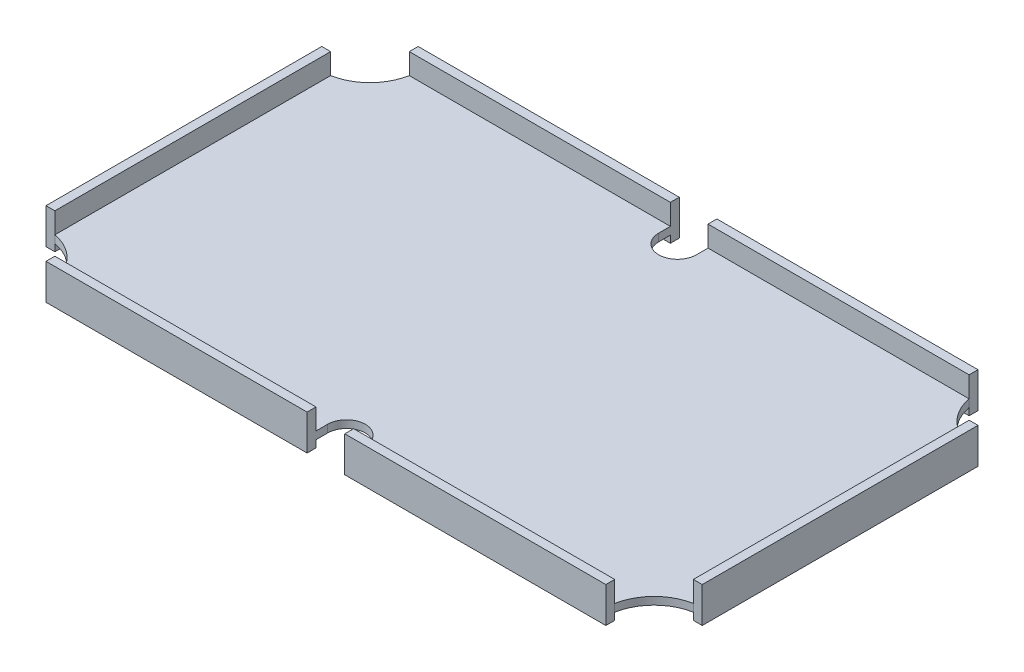
SolidWorks part; units mm, degrees
ref_plane "Alzado" through (0, 0, 0) normal (0, 0, 1) x (1, 0, 0)
ref_plane "Planta" through (0, 0, 0) normal (0, 1, 0) x (1, 0, 0)
ref_plane "Vista lateral" through (0, 0, 0) normal (1, 0, 0) x (0, 0, -1)
sketch "Croquis1" plane through (0, 0, 0) normal (0, 1, 0) x (1, 0, 0)
  line L1 (-46.2, 26.2) -> (46.2, 26.2)
  line L2 (-46.2, 26.2) -> (-46.2, -26.2)
  line L3 (-46.2, -26.2) -> (46.2, -26.2)
  line L4 (46.2, 26.2) -> (46.2, -26.2)
  line L5 (-46.2, 26.2) -> (46.2, -26.2) construction
  line L6 (-46.2, -26.2) -> (46.2, 26.2) construction
  point P0 (0, 0)
  dimension "D1" = 92.4
  dimension "D2" = 52.4
extrude "Saliente-Extruir1" add sketch "Croquis1" along normal blind 5
sketch "Croquis2" plane through (0, 5, 0) normal (0, 1, 0) x (1, 0, 0)
  line L0 (-46.2, 26.2) -> (-46.2, -26.2) construction
  line L1 (44.95, 24.95) -> (-44.95, 24.95)
  line L2 (44.95, 24.95) -> (44.95, -24.95)
  line L3 (44.95, -24.95) -> (-44.95, -24.95)
  line L4 (-44.95, 24.95) -> (-44.95, -24.95)
  line L5 (44.95, 24.95) -> (-44.95, -24.95) construction
  line L6 (44.95, -24.95) -> (-44.95, 24.95) construction
  line L7 (-46.2, -26.2) -> (46.2, -26.2) construction
  point P0 (0, 0)
  dimension "D1" = 1.25
  dimension "D2" = 1.25
extrude "Cortar-Extruir1" cut sketch "Croquis2" against normal blind 2.93
sketch "Croquis3" plane through (0, 2.07, 0) normal (0, 1, 0) x (1, 0, 0)
  line L0 (0, -20.66) -> (0, -26.2) construction
  line L2 (-46.2, -26.2) -> (46.2, -26.2) construction
  line L3 (-44.95, -24.95) -> (44.95, -24.95) construction
  line L4 (2.65, -23.31) -> (-2.65, -23.31) construction
  line L5 (2.65, -23.31) -> (2.65, -26.2)
  line L6 (2.65, -26.2) -> (-2.65, -26.2)
  line L7 (-2.65, -23.31) -> (-2.65, -26.2)
  line L8 (2.65, -23.31) -> (-2.65, -26.2) construction
  line L9 (2.65, -26.2) -> (-2.65, -23.31) construction
  arc A0 (-2.65, -23.31) -> (2.65, -23.31) centre (0, -23.31) cw
  point P3 (0, -24.755)
  dimension "D1" = 5.3
  dimension "D2" = 1.64
extrude "Cortar-Extruir2" cut sketch "Croquis3" against normal up to surface and the other way up to surface
sketch "Croquis4" plane through (0, 2.07, 0) normal (0, 1, 0) x (1, 0, 0)
  line L0 (-46.2, 26.2) -> (-46.2, -26.2) construction
  line L1 (-46.2, -26.2) -> (-2.65, -26.2) construction
  line L2 (-46.2, 26.2) -> (-46.2, -26.2) construction
  line L3 (-46.2, -26.2) -> (-2.65, -26.2) construction
  line L5 (-46.2, -19.4142) -> (-46.2, -26.2)
  line L6 (-46.2, -26.2) -> (-39.4142, -26.2)
  line L7 (-44.95, 24.95) -> (-44.95, -24.95) construction
  line L8 (-44.95, -24.95) -> (-2.65, -24.95) construction
  line L9 (-44.95, 24.95) -> (-44.95, -24.95) construction
  line L10 (-44.95, -24.95) -> (-2.65, -24.95) construction
  line L11 (-39.4142, -24.95) -> (-39.4142, -26.2)
  line L12 (-44.95, -19.4142) -> (-46.2, -19.4142)
  arc A0 (-46.2, -19.3) -> (-39.3, -26.2) centre (-46.2, -26.2) cw construction
  arc A2 (-39.4142, -24.95) -> (-44.95, -19.4142) centre (-46.2, -26.2) ccw
  dimension "D1" = 6.9
extrude "Cortar-Extruir3" cut sketch "Croquis4" against normal up to surface and the other way up to surface
mirror "Simetría1" about plane through (0, 0, 0) normal (1, 0, 0) of "Cortar-Extruir3"
mirror "Simetría2" about plane through (0, 0, 0) normal (0, 0, 1) of "Simetría1", "Cortar-Extruir3"
mirror "Simetría3" about plane through (0, 0, 0) normal (0, 0, 1) of "Cortar-Extruir2"
sketch "Croquis6" plane through (0, 0, 0) normal (0, -1, 0) x (1, 0, 0)
  line L0 (3.9, -23.31) -> (3.9, -24.95)
  line L1 (3.9, -24.95) -> (38.1642, -24.95)
  line L4 (44.95, -18.1642) -> (44.95, 18.1642)
  line L7 (38.1642, 24.95) -> (3.9, 24.95)
  line L10 (-3.9, 24.95) -> (-38.1642, 24.95)
  line L13 (-44.95, 18.1642) -> (-44.95, -18.1642)
  line L16 (-38.1642, -24.95) -> (-3.9, -24.95)
  line L18 (2.65, -23.31) -> (2.65, -26.2)
  line L19 (2.65, -26.2) -> (39.4142, -26.2)
  line L20 (39.4142, -26.2) -> (39.4142, -24.95)
  line L21 (44.95, -19.4142) -> (46.2, -19.4142)
  line L22 (46.2, -19.4142) -> (46.2, 19.4142)
  line L23 (46.2, 19.4142) -> (44.95, 19.4142)
  line L24 (39.4142, 24.95) -> (39.4142, 26.2)
  line L25 (39.4142, 26.2) -> (2.65, 26.2)
  line L26 (2.65, 26.2) -> (2.65, 23.31)
  line L27 (-2.65, 23.31) -> (-2.65, 26.2)
  line L28 (-2.65, 26.2) -> (-39.4142, 26.2)
  line L29 (-39.4142, 26.2) -> (-39.4142, 24.95)
  line L30 (-44.95, 19.4142) -> (-46.2, 19.4142)
  line L31 (-46.2, 19.4142) -> (-46.2, -19.4142)
  line L32 (-46.2, -19.4142) -> (-44.95, -19.4142)
  line L33 (-39.4142, -24.95) -> (-39.4142, -26.2)
  line L34 (-39.4142, -26.2) -> (-2.65, -26.2)
  line L35 (-2.65, -26.2) -> (-2.65, -23.31)
  line L36 (2.65, -23.31) -> (2.65, -24.95)
  line L53 (-2.65, -24.95) -> (-2.65, -23.31)
  line L54 (-3.9, 24.95) -> (-2.65, 24.95)
  line L55 (3.9, 24.95) -> (2.65, 24.95)
  line L56 (-3.9, 23.31) -> (-3.9, 24.95) construction
  line L57 (-2.65, 23.31) -> (-2.65, 26.2) construction
  line L58 (3.9, 24.95) -> (3.9, 23.31) construction
  line L59 (38.1642, 24.95) -> (39.4142, 24.95)
  line L60 (2.65, 26.2) -> (2.65, 23.31) construction
  line L61 (38.1642, 24.8406) -> (38.1642, 24.95) construction
  line L62 (44.95, 18.1642) -> (44.8406, 18.1642) construction
  line L63 (44.95, 18.1642) -> (44.95, 19.4142)
  line L64 (38.1642, -24.95) -> (39.4142, -24.95)
  line L65 (44.8406, -18.1642) -> (44.95, -18.1642) construction
  line L66 (38.1642, -24.95) -> (38.1642, -24.8406) construction
  line L67 (44.95, -18.1642) -> (44.95, -19.4142)
  line L68 (3.9, -24.95) -> (2.65, -24.95)
  line L69 (-3.9, -24.95) -> (-2.65, -24.95)
  line L70 (-44.95, -18.1642) -> (-44.95, -19.4142)
  line L71 (-39.4142, -24.95) -> (-38.1642, -24.95)
  line L72 (-44.95, 18.1642) -> (-44.95, 19.4142)
  line L73 (-38.1642, 24.95) -> (-39.4142, 24.95)
  line L74 (-2.65, 24.95) -> (-2.65, 23.31)
  line L75 (-38.1642, 24.95) -> (-38.1642, 24.8406) construction
  line L76 (-44.8406, 18.1642) -> (-44.95, 18.1642) construction
  line L77 (-44.95, -18.1642) -> (-44.8406, -18.1642) construction
  line L78 (-38.1642, -24.8406) -> (-38.1642, -24.95) construction
  line L79 (-46.2, -19.4142) -> (-44.95, -19.4142) construction
  line L80 (-46.2, 19.4142) -> (-46.2, -19.4142) construction
  line L81 (-39.4142, -26.2) -> (-2.65, -26.2) construction
  line L82 (-39.4142, -24.95) -> (-39.4142, -26.2) construction
  line L83 (-2.65, -26.2) -> (-2.65, -23.31) construction
  line L84 (-3.9, -24.95) -> (-3.9, -23.31) construction
  line L85 (2.65, -26.2) -> (39.4142, -26.2) construction
  line L86 (2.65, -23.31) -> (2.65, -26.2) construction
  line L87 (-44.95, 19.4142) -> (-46.2, 19.4142) construction
  line L88 (-39.4142, 26.2) -> (-39.4142, 24.95) construction
  line L89 (-2.65, 26.2) -> (-39.4142, 26.2) construction
  line L90 (39.4142, 26.2) -> (2.65, 26.2) construction
  line L91 (39.4142, 24.95) -> (39.4142, 26.2) construction
  line L92 (46.2, 19.4142) -> (44.95, 19.4142) construction
  line L93 (46.2, -19.4142) -> (46.2, 19.4142) construction
  line L94 (44.95, -19.4142) -> (46.2, -19.4142) construction
  line L95 (39.4142, -26.2) -> (39.4142, -24.95) construction
  line L96 (2.65, 23.31) -> (2.65, 26.2) construction
  line L97 (2.65, 23.31) -> (2.65, 24.95)
  arc A6 (44.95, -19.4142) -> (39.4142, -24.95) centre (46.2, -26.2) ccw
  arc A7 (39.4142, 24.95) -> (44.95, 19.4142) centre (46.2, 26.2) ccw
  arc A8 (-2.65, 23.31) -> (2.65, 23.31) centre (0, 23.31) ccw
  arc A9 (-44.95, 19.4142) -> (-39.4142, 24.95) centre (-46.2, 26.2) ccw
  arc A10 (-39.4142, -24.95) -> (-44.95, -19.4142) centre (-46.2, -26.2) ccw
  arc A11 (2.65, -23.31) -> (-2.65, -23.31) centre (0, -23.31) ccw
  arc A12 (44.95, -19.4142) -> (39.4142, -24.95) centre (46.2, -26.2) ccw
  arc A13 (39.4142, 24.95) -> (44.95, 19.4142) centre (46.2, 26.2) ccw
  arc A15 (-44.95, 19.4142) -> (-39.4142, 24.95) centre (-46.2, 26.2) ccw
  arc A16 (-39.4142, -24.95) -> (-44.95, -19.4142) centre (-46.2, -26.2) ccw
  arc A17 (2.65, -23.31) -> (-2.65, -23.31) centre (0, -23.31) ccw
  arc A18 (-3.9, 23.31) -> (3.9, 23.31) centre (0, 23.31) ccw construction
  arc A19 (-2.65, 23.31) -> (2.65, 23.31) centre (0, 23.31) ccw construction
  arc A20 (38.1642, 24.8406) -> (44.8406, 18.1642) centre (46.2, 26.2) ccw construction
  arc A21 (44.8406, -18.1642) -> (38.1642, -24.8406) centre (46.2, -26.2) ccw construction
  arc A22 (-44.8406, 18.1642) -> (-38.1642, 24.8406) centre (-46.2, 26.2) ccw construction
  arc A23 (-38.1642, -24.8406) -> (-44.8406, -18.1642) centre (-46.2, -26.2) ccw construction
  arc A24 (3.9, -23.31) -> (-3.9, -23.31) centre (0, -23.31) ccw construction
  arc A25 (-2.65, 23.31) -> (2.65, 23.31) centre (0, 23.31) ccw construction
  arc A26 (-2.65, 23.31) -> (2.65, 23.31) centre (0, 23.31) ccw
  dimension "D1" = 0
  dimension "D2" = 1.25
extrude "Cortar-Extruir5" cut sketch "Croquis6" against normal blind 1
sketch "Croquis7" plane through (0, 1, 0) normal (0, -1, 0) x (1, 0, 0)
  line L0 (-44.95, -19.4142) -> (-44.95, 19.4142) construction
  line L1 (-44.95, -12.31) -> (44.95, -12.31)
  line L2 (-44.95, -12.31) -> (-44.95, -16.82)
  line L3 (-44.95, -16.82) -> (44.95, -16.82)
  line L4 (44.95, -12.31) -> (44.95, -16.82)
  line L5 (44.95, 19.4142) -> (44.95, -19.4142) construction
  line L6 (-39.4142, -24.95) -> (-2.65, -24.95) construction
  dimension "D1" = 8.13
  dimension "D2" = 4.51
extrude "Saliente-Extruir2" add sketch "Croquis7" along normal blind 1.24
mirror "Simetría4" about plane through (0, 0, 0) normal (0, 0, 1) of "Saliente-Extruir2"
